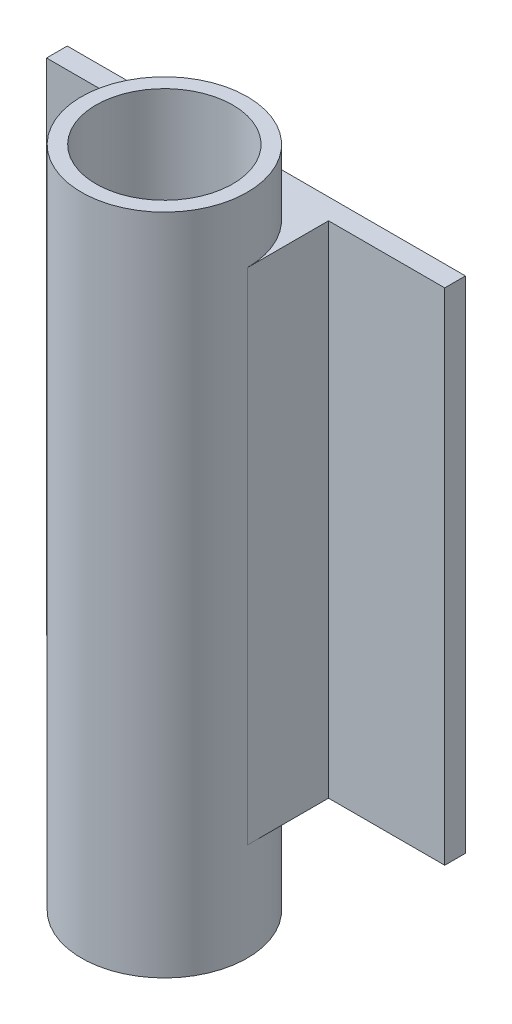
SolidWorks part; units mm, degrees
other "DetailItem2"
other "DetailItem3"
material "6061 Alloy"
ref_plane "Front Plane" through (0, 0, 0) normal (0, 0, 1) x (1, 0, 0)
ref_plane "Top Plane" through (0, 0, 0) normal (0, 1, 0) x (1, 0, 0)
ref_plane "Right Plane" through (0, 0, 0) normal (1, 0, 0) x (0, 0, -1)
sketch "Sketch11" plane through (0, 0, 0) normal (0, 0, 1) x (1, 0, 0)
  line L0 (0, 0) -> (0, 109.6398) construction
  line L1 (0, 0) -> (-89.1372, 0) construction
sketch "Sketch12" plane through (0, 0, 0) normal (0, 0, 1) x (1, 0, 0)
  line L0 (-25.4, 0) -> (-25.4, 203.2)
  line L1 (200000, 0) -> (-200089.1372, 0) construction
  line L4 (-20.955, 0) -> (-25.4, 0)
  line L5 (-20.955, 0) -> (-20.955, 38.1)
  line L6 (-20.955, 38.1) -> (-19.177, 38.1)
  line L7 (-19.177, 38.1) -> (-19.177, 165.1)
  line L8 (-19.177, 165.1) -> (-20.955, 165.1)
  line L9 (-20.955, 165.1) -> (-20.955, 203.2)
  line L10 (-20.955, 203.2) -> (-25.4, 203.2)
  line L12 (0, -200000) -> (0, 200109.6398) construction
  line L13 (-20.955, 203.2) -> (-15.875, 203.2) construction
  line L14 (-15.875, 203.2) -> (-15.875, 0) construction
  line L15 (-15.875, 0) -> (-20.955, 0) construction
  dimension "D1" = 25.4
  dimension "D2" = 20.955
  dimension "D3" = 19.177
  dimension "D4" = 38.1
  dimension "D5" = 203.2
  dimension "D6" = 4.445
  dimension "D7" = 15.875
revolve "Revolve1" add sketch "Sketch12" angle 360 about L0
ref_plane "mideplane" through (0, 101.6, 0) normal (0, -1, 0) x (-1, 0, 0)
ref_plane "top pipe plane" through (0, 30, 0) normal (0, -1, 0) x (-1, 0, 0)
ref_plane "bottom pipe plane" through (0, 183.2, 0) normal (0, 1, 0) x (1, 0, 0)
ref_plane "pipe support midplane" through (0, 106.6, 0) normal (0, -1, 0) x (-1, 0, 0)
sketch "Sketch13" plane through (0, 30, 0) normal (0, -1, 0) x (-1, 0, 0)
  line L0 (0, 0) -> (0, 24.9) construction
  line L1 (0, 24.9) -> (0, 25.4) construction
  line L2 (61, 31.25) -> (-61, 31.25)
  line L3 (61, 31.25) -> (61, 24.9)
  line L4 (61, 24.9) -> (-61, 24.9)
  line L5 (-61, 31.25) -> (-61, 24.9)
  line L6 (-38, 24.9) -> (-38, 31.25) construction
  line L7 (0, 25.4) -> (0, 31.25) construction
  line L8 (-33, 24.9) -> (-33, 31.25) construction
  line L9 (-43, 24.9) -> (-43, 31.25) construction
  line L10 (-43, 28.075) -> (-33, 28.075) construction
  line L11 (-33, 28.075) -> (-30, 28.075) construction
  line L12 (-30, 24.9) -> (-30, 31.25) construction
  line L13 (-43, 28.075) -> (-46, 28.075) construction
  line L14 (-46, 31.25) -> (-46, 24.9) construction
  line L15 (20, 24.9) -> (20, 15.6576)
  line L16 (-20, 24.9) -> (-20, 15.6576)
  line L17 (23.175, 24.9) -> (23.175, 10.3961)
  line L18 (-23.175, 24.9) -> (-23.175, 10.3961)
  line L19 (25.4, 0) -> (25.4, 24.9)
  line L20 (-25.4, 0) -> (-25.4, 24.9)
  circle A0 centre (0, 0) radius 25.4 construction
  circle A1 centre (0, 0) radius 25.4
  point P18 (-38, 28.075)
  point P35 (-23.175, 17.6481)
  dimension "D1" = 6.35
  dimension "D2" = 0.5
  dimension "D3" = 10
  dimension "D4" = 16
  dimension "D5" = 30
  dimension "D6" = 15
  dimension "D7" = 40
  dimension "D8" = 3.175
  dimension "D9" = 3.175
extrude "Boss-Extrude1" add sketch "Sketch13" against normal up to surface (153.2 mm away) contours A1 L4 L3 L2 L5 | A1 L16 L4 L18 | A1 L17 L4 L15 | A1 L4 L16 | A1 L15 L4 | A1 L18 L4 L20 | A1 L19 L4 L17
